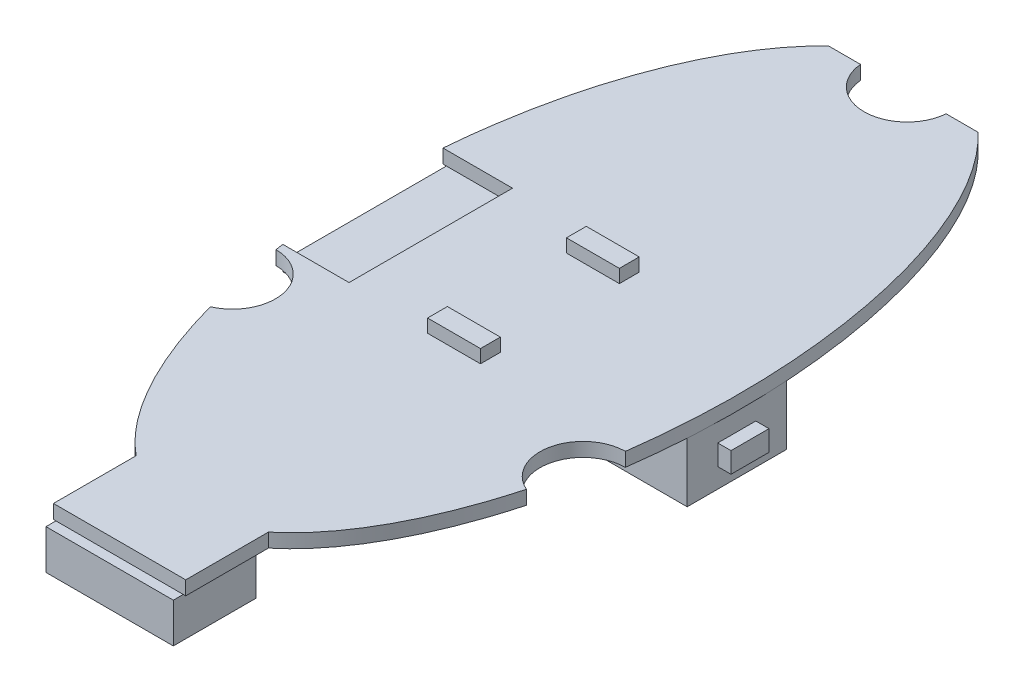
SolidWorks part; units mm, degrees
other "TactSwitch"
ref_plane "Front Plane" through (0, 0, 0) normal (0, 0, 1) x (1, 0, 0)
ref_plane "Top Plane" through (0, 0, 0) normal (0, 1, 0) x (1, 0, 0)
ref_plane "Right Plane" through (0, 0, 0) normal (1, 0, 0) x (0, 0, -1)
sketch "Sketch1" plane through (0, 0, 0) normal (0, 1, 0) x (1, 0, 0)
  line L1 (0, 0) -> (0, -66.7312) construction
  line L2 (-5.7323, 26.6377) -> (-3.2896, 26.6377)
  line L3 (-5.08, -27.2103) -> (-5.08, -33.5603)
  line L4 (-5.08, -33.5603) -> (5.08, -33.5603)
  line L5 (5.08, -27.2103) -> (5.08, -33.5603)
  line L7 (3.2896, 26.6377) -> (5.7323, 26.6377)
  arc A0 (-12.1394, -14.4555) -> (-13.4182, -8.1283) centre (-13.462, -11.43) ccw
  arc A1 (13.4182, -8.1283) -> (12.1394, -14.4555) centre (13.462, -11.43) ccw
  arc A2 (-3.2896, 26.6377) -> (3.2896, 26.6377) centre (0, 26.924) ccw
  ellipse E0 centre (0, 0) end of major axis (0, 29.21) minor radius 13.97 (5.08, -27.2103) -> (12.1394, -14.4555) ccw
  ellipse E1 centre (0, 0) end of major axis (0, 29.21) minor radius 13.97 (-12.1394, -14.4555) -> (-5.08, -27.2103) ccw
  ellipse E2 centre (0, 0) end of major axis (0, 29.21) minor radius 13.97 (13.4182, -8.1283) -> (5.7323, 26.6377) ccw
  ellipse E3 centre (0, 0) end of major axis (0, 29.21) minor radius 13.97 (-5.7323, 26.6377) -> (-13.4182, -8.1283) ccw
  dimension "D4" = 26.924
  dimension "D8" = 3.302
  dimension "D1" = 27.94
  dimension "D2" = 58.42
  dimension "D3" = 6.35
  dimension "D5" = 11.43
  dimension "D6" = 10.16
  dimension "D7" = 53.848
  dimension "D9" = 26.924
extrude "BareBoard" add sketch "Sketch1" along normal blind 1.0668
sketch "Sketch2" plane through (0, 0, 0) normal (0, -1, 0) x (1, 0, 0)
  line L1 (-4.8895, 34.3223) -> (4.8895, 34.3223)
  line L2 (-4.8895, 34.3223) -> (-4.8895, 27.9723)
  line L3 (-4.8895, 27.9723) -> (4.8895, 27.9723)
  line L4 (4.8895, 34.3223) -> (4.8895, 27.9723)
  line L5 (0, 0) -> (0, 28.5084) construction
  line L7 (-5.08, 33.5603) -> (5.08, 33.5603) construction
  dimension "D1" = 9.779
  dimension "D2" = 6.35
  dimension "D3" = 0.762
extrude "USB" add sketch "Sketch2" along normal blind 3.048 separate body
sketch "Sketch3" plane through (0, 1.0668, 0) normal (0, 1, 0) x (1, 0, 0)
  line L0 (0, 0) -> (0, 26.2894) construction
  line L1 (-2.032, 4.318) -> (2.032, 4.318)
  line L2 (-2.032, 4.318) -> (-2.032, 2.794)
  line L3 (-2.032, 2.794) -> (2.032, 2.794)
  line L4 (2.032, 4.318) -> (2.032, 2.794)
  line L5 (-2.032, -6.35) -> (2.032, -6.35)
  line L6 (-2.032, -6.35) -> (-2.032, -7.874)
  line L7 (-2.032, -7.874) -> (2.032, -7.874)
  line L8 (2.032, -6.35) -> (2.032, -7.874)
  dimension "D1" = 4.064
  dimension "D2" = 1.524
  dimension "D3" = 2.794
  dimension "D4" = 6.35
extrude "SideFire LEDs" add sketch "Sketch3" along normal blind 1.016 separate body
sketch "Sketch4" plane through (0, 0, 0) normal (0, -1, 0) x (1, 0, 0)
  line L1 (-13.4995, 7.5169) -> (6.8205, 7.5169)
  line L2 (-13.4995, 7.5169) -> (-13.4995, -5.1831)
  line L3 (-13.4995, -5.1831) -> (6.8205, -5.1831)
  line L4 (6.8205, 7.5169) -> (6.8205, -5.1831)
  ellipse E2 centre (0, 0) end of major axis (0, -29.21) minor radius 13.97 (5.7323, -26.6377) -> (13.4182, 8.1283) ccw construction
  dimension "D1" = 12.7
  dimension "D3" = 20.32
extrude "BLE Radio" add sketch "Sketch4" along normal blind 2.794 separate body
sketch "Sketch5" plane through (0, -2.794, 0) normal (0, -1, 0) x (1, 0, 0)
  line L0 (-13.4995, -5.1831) -> (6.8205, -5.1831) construction
  line L1 (-13.4995, 7.5169) -> (-7.1495, 7.5169)
  line L2 (-13.4995, 7.5169) -> (-13.4995, -5.1831)
  line L3 (-13.4995, -5.1831) -> (-7.1495, -5.1831)
  line L4 (-7.1495, 7.5169) -> (-7.1495, -5.1831)
  dimension "D1" = 6.35
extrude "Cut-Extrude1" cut sketch "Sketch5" against normal blind 2.032
sketch "Sketch6" plane through (0, 1.0668, 0) normal (0, 1, 0) x (1, 0, 0)
  line L0 (6.8205, -7.5169) -> (-13.4995, -7.5169) construction
  line L1 (-21.121, 5.04) -> (-8.421, 5.04)
  line L2 (-21.121, 5.04) -> (-21.121, -7.5169)
  line L3 (-21.121, -7.5169) -> (-8.421, -7.5169)
  line L4 (-8.421, 5.04) -> (-8.421, -7.5169)
  dimension "D1" = 12.7
  dimension "D2" = 8.421
extrude "Cut-Extrude2" cut sketch "Sketch6" against normal up to surface (1.0668 mm away) up to face at (0, 0, 4.8897)
sketch "Sketch7" plane through (0, 0, 0) normal (0, -1, 0) x (1, 0, 0)
  line L0 (0, 0) -> (31.0719, 0) construction
  line L1 (7.493, 3.81) -> (13.843, 3.81)
  line L2 (7.493, 3.81) -> (7.493, -3.81)
  line L3 (7.493, -3.81) -> (13.843, -3.81)
  line L4 (13.843, 3.81) -> (13.843, -3.81)
  line L5 (7.493, 3.81) -> (13.843, -3.81) construction
  line L6 (7.493, -3.81) -> (13.843, 3.81) construction
  point P0 (10.668, 0)
  dimension "D1" = 7.62
  dimension "D2" = 6.35
  dimension "D3" = 10.668
extrude "Boss-Extrude1" add sketch "Sketch7" along normal blind 4.572 separate body
sketch "Sketch8" plane through (13.843, 0, 0) normal (1, 0, 0) x (0, 0, -1)
  line L0 (3.81, -2.286) -> (-3.81, -2.286) construction
  line L1 (3.81, -4.572) -> (3.81, 0) construction
  line L2 (-3.81, -4.572) -> (-3.81, 0) construction
  line L3 (0, -4.572) -> (0, 0) construction
  line L4 (3.81, -4.572) -> (-3.81, -4.572) construction
  line L5 (3.81, 0) -> (-3.81, 0) construction
  line L7 (-1.4605, -1.4986) -> (1.4605, -1.4986)
  line L8 (-1.4605, -1.4986) -> (-1.4605, -3.0734)
  line L9 (-1.4605, -3.0734) -> (1.4605, -3.0734)
  line L10 (1.4605, -1.4986) -> (1.4605, -3.0734)
  line L11 (-1.4605, -1.4986) -> (1.4605, -3.0734) construction
  line L12 (-1.4605, -3.0734) -> (1.4605, -1.4986) construction
  point P12 (0, -2.286)
  dimension "D1" = 1.5748
  dimension "D2" = 2.921
extrude "Boss-Extrude2" add sketch "Sketch8" along normal blind 1.016
